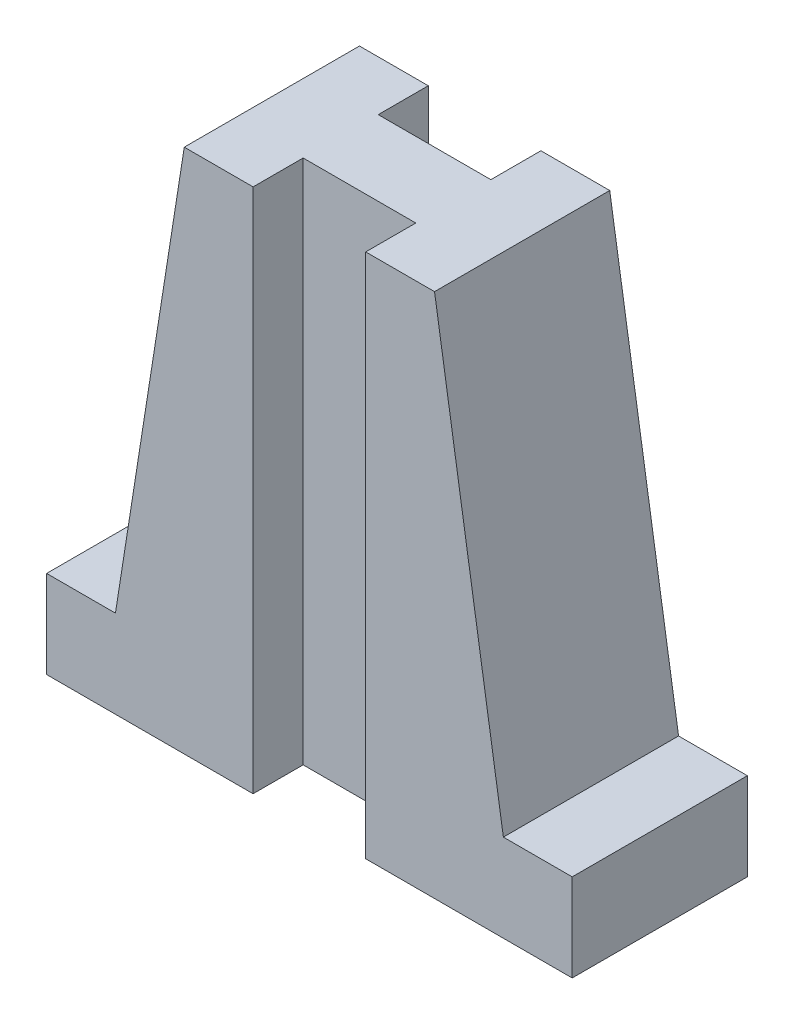
SolidWorks part; units mm, degrees
ref_plane "Alzado" through (0, 0, 0) normal (0, 0, 1) x (1, 0, 0)
ref_plane "Planta" through (0, 0, 0) normal (0, 1, 0) x (1, 0, 0)
ref_plane "Vista lateral" through (0, 0, 0) normal (1, 0, 0) x (0, 0, -1)
sketch "Croquis1" plane through (0, 0, 0) normal (0, 0, 1) x (1, 0, 0)
  line L0 (-20, 35) -> (20, 35)
  line L1 (-42, -35) -> (-31, -35)
  line L2 (-42, -35) -> (-42, -49)
  line L3 (-42, -49) -> (42, -49)
  line L4 (42, -35) -> (42, -49)
  line L5 (-31, -35) -> (-20, 35)
  line L6 (20, 35) -> (31, -35)
  line L7 (31, -35) -> (42, -35)
  point P6 (0, 35)
  point P7 (0, -49)
  point P10 (25.5, 0)
  point P12 (0, 0)
  dimension "D1" = 84
  dimension "D2" = 14
  dimension "D3" = 40
  dimension "D4" = 70
  dimension "D5" = 62
extrude "Saliente-Extruir1" add sketch "Croquis1" against normal blind 28
sketch "Croquis2" plane through (0, 35, 0) normal (0, 1, 0) x (1, 0, 0)
  line L5 (-9, 8) -> (9, 8)
  line L6 (-9, 8) -> (-9, 0)
  line L7 (-9, 0) -> (9, 0)
  line L8 (9, 8) -> (9, 0)
  line L9 (-42, 14) -> (42, 14) construction
  line L10 (-42, 28) -> (-42, 0) construction
  line L11 (42, 28) -> (42, 0) construction
  line L12 (-9, 20) -> (-9, 28)
  line L13 (-9, 28) -> (9, 28)
  line L14 (9, 20) -> (9, 28)
  line L15 (-9, 20) -> (9, 20)
  point P12 (0, 0)
  dimension "D1" = 12
  dimension "D2" = 18
extrude "Cortar-Extruir1" cut sketch "Croquis2" against normal through all
